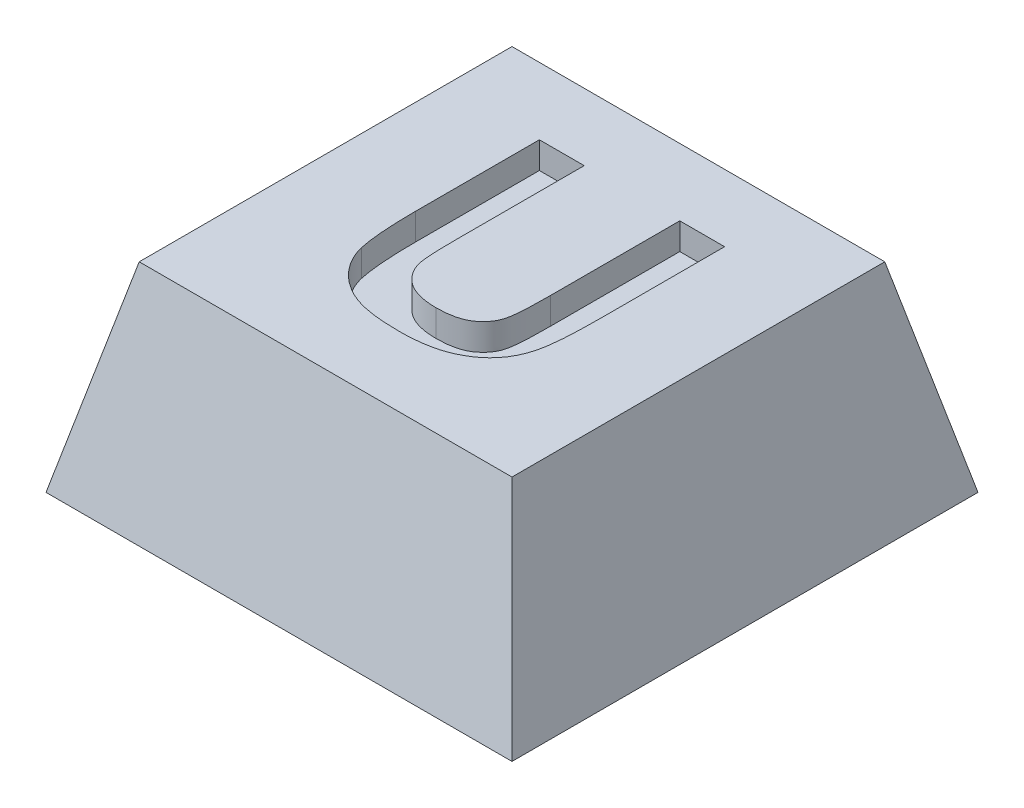
SolidWorks part; units mm, degrees
ref_plane "Front Plane" through (0, 0, 0) normal (0, 0, 1) x (1, 0, 0)
ref_plane "Top Plane" through (0, 0, 0) normal (0, 1, 0) x (1, 0, 0)
ref_plane "Right Plane" through (0, 0, 0) normal (1, 0, 0) x (0, 0, -1)
sketch "Sketch1" plane through (0, 0, 0) normal (0, 1, 0) x (1, 0, 0)
  line L1 (0, 0) -> (7, 0)
  line L2 (0, 0) -> (0, 7)
  line L3 (0, 7) -> (7, 7)
  line L4 (7, 0) -> (7, 7)
  dimension "D1" = 7
  dimension "D2" = 7
extrude "Boss-Extrude1" add sketch "Sketch1" along normal blind 3
sketch "Sketch2" plane through (0, 0, 0) normal (0, 0, 1) x (1, 0, 0)
  line L0 (0, 0) -> (0.7, 3)
  line L1 (0, 3) -> (7, 3) construction
  line L2 (0.7, 3) -> (0, 3)
  line L3 (0, 3) -> (0, 0)
  line L4 (7, 0) -> (6.3, 3)
  line L5 (6.3, 3) -> (7, 3)
  line L6 (7, 3) -> (7, 0)
  dimension "D1" = 0.7
  dimension "D2" = 0.7
extrude "Cut-Extrude1" cut sketch "Sketch2" against normal blind 7
sketch "Sketch3" plane through (0, 0, 0) normal (1, 0, 0) x (0, 0, -1)
  line L0 (0, 0) -> (0.7, 3)
  line L1 (7, 3) -> (0, 3) construction
  line L2 (0.7, 3) -> (0, 3)
  line L3 (0, 3) -> (0, 0)
  line L4 (7, 3) -> (6.3, 3)
  line L5 (6.3, 3) -> (7, 0)
  line L6 (7, 3) -> (7, 0)
  dimension "D1" = 0.7
  dimension "D2" = 0.7
extrude "Cut-Extrude2" cut sketch "Sketch3" along normal blind 11
sketch "Sketch4" plane through (0, 0, 0) normal (0, -1, 0) x (1, 0, 0)
  line L0 (3.5, 0) -> (3.5, -7) construction
  line L1 (0, 0) -> (7, 0) construction
  line L2 (7, -7) -> (0, -7) construction
  line L3 (0, -3.5) -> (7, -3.5) construction
  line L4 (0, -7) -> (0, 0) construction
  line L5 (7, 0) -> (7, -7) construction
  circle A0 centre (3.5, -3.5) radius 1.8
  dimension "D1" = 3.6
extrude "Cut-Extrude3" cut sketch "Sketch4" against normal blind 0.8
sketch "Sketch5" plane through (0, 3, 0) normal (0, 1, 0) x (1, 0, 0)
  text T0 "U" font "Arial" height 3.5
extrude "Cut-Extrude4" cut sketch "Sketch5" against normal blind 0.4
